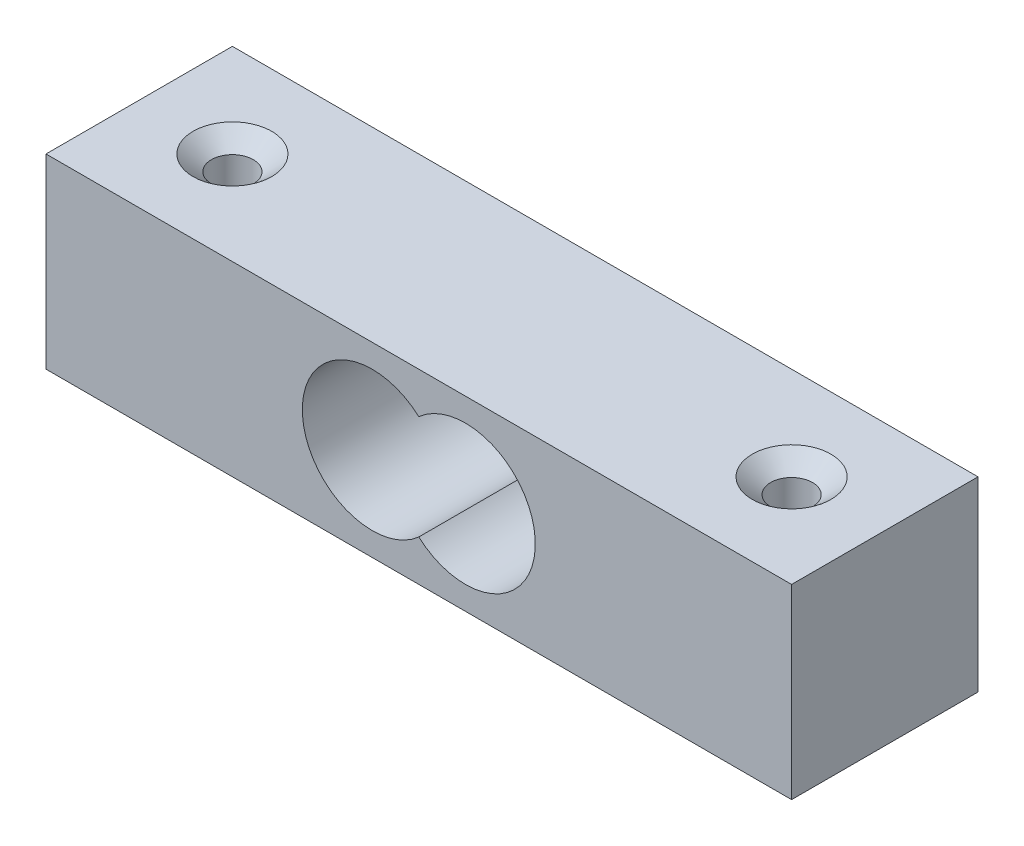
SolidWorks part; units mm, degrees
material "6063-O, Extruded Rod (SS)"
ref_plane "Front Plane" through (0, 0, 0) normal (0, 0, 1) x (1, 0, 0)
ref_plane "Top Plane" through (0, 0, 0) normal (0, 1, 0) x (1, 0, 0)
ref_plane "Right Plane" through (0, 0, 0) normal (1, 0, 0) x (0, 0, -1)
sketch "Sketch1" plane through (0, 0, 0) normal (0, 1, 0) x (1, 0, 0)
  line L1 (-40, -10) -> (40, -10)
  line L2 (-40, -10) -> (-40, 10)
  line L3 (-40, 10) -> (40, 10)
  line L4 (40, -10) -> (40, 10)
  line L5 (-40, -10) -> (40, 10) construction
  line L6 (-40, 10) -> (40, -10) construction
  point P0 (0, 0)
  dimension "D1" = 20
  dimension "D2" = 80
extrude "Boss-Extrude1" add sketch "Sketch1" along normal blind 20
sketch "Sketch2" plane through (0, 0, 10) normal (0, 0, 1) x (1, 0, 0)
  line L0 (0, 0) -> (0, 20) construction
  line L1 (-40, 0) -> (40, 0) construction
  line L2 (-40, 20) -> (40, 20) construction
  line L3 (-5, 10) -> (5, 10) construction
  circle A0 centre (5, 10) radius 7.5
  circle A1 centre (-5, 10) radius 7.5
  point P9 (0, 10)
  dimension "D1" = 10
extrude "Cut-Extrude1" cut sketch "Sketch2" against normal blind 20 contours A1 A0 | A0 A1 | A0 A1
sketch "Sketch3" plane through (0, 20, 0) normal (0, 1, 0) x (1, 0, 0)
  line L0 (0, 10) -> (0, -10) construction
  line L1 (40, 10) -> (-40, 10) construction
  line L2 (-40, -10) -> (40, -10) construction
  line L3 (-30, 0) -> (30, 0)
  point P7 (0, 10)
  point P10 (0, 0)
hole_wizard "CSK for #8 Flat Head Machine Screw (100)1" positions "Sketch4" profile "Sketch6" countersink size "#8" standard "ANSI Inch" end condition through all
sketch "Sketch4" plane through (0, 20, 0) normal (0, 1, 0) x (1, 0, 0)
  point P0 (-30, 0)
  point P3 (30, 0)
sketch "Sketch6" plane through (-30, 20, 0) normal (1, 0, 0) x (0, 0, 1)
  line L0 (0, 0) -> (0, 20)
  line L1 (0, 20) -> (2.2479, 20)
  line L2 (2.2479, 20) -> (2.2479, 1.6518)
  line L3 (2.2479, 1.6518) -> (4.2164, 0)
  line L5 (4.2164, 0) -> (0, 0)
  line L6 (-2.2479, 1.6518) -> (-4.2164, 0) construction
  line L11 (0, -6.35) -> (0, 107.95) construction
  dimension "Thru Hole Dia." = 4.4958
  dimension "Thru Hole Depth" = 20
  dimension "Near C'Sink Dia." = 8.4328
  dimension "Near C'Sink Angle" = 100
